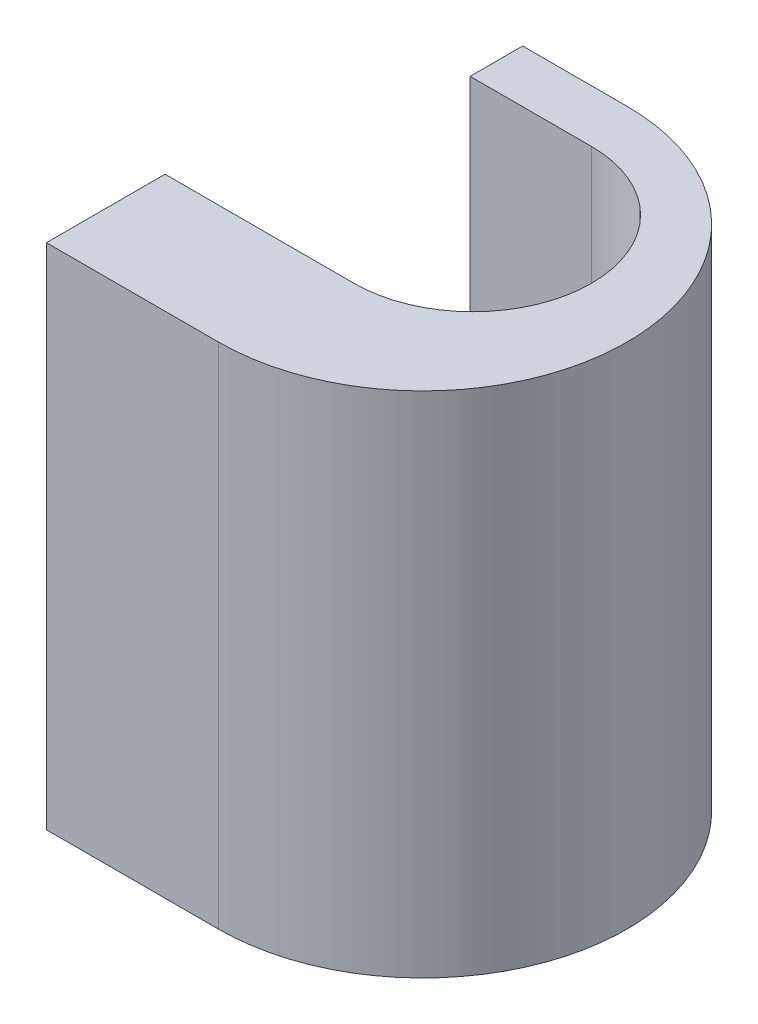
SolidWorks part; units mm, degrees
ref_plane "Front Plane" through (0, 0, 0) normal (0, 0, 1) x (1, 0, 0)
ref_plane "Top Plane" through (0, 0, 0) normal (0, 1, 0) x (1, 0, 0)
ref_plane "Right Plane" through (0, 0, 0) normal (1, 0, 0) x (0, 0, -1)
sketch "Sketch1" plane through (0, 0, 0) normal (0, 1, 0) x (1, 0, 0)
  line L0 (-2.9358, -0.5334) -> (-2.9358, 2.9666)
  line L1 (-2.9358, -0.5334) -> (-2.9358, -4.0334)
  line L5 (-2.9358, -4.0334) -> (0.6437, -4.0334)
  line L6 (-2.9358, 2.9666) -> (0.6437, 2.9666)
  circle A2 centre (0, 0) radius 1.7
  arc A4 (0.6437, 2.9666) -> (0.6437, -4.0334) centre (0.6437, -0.5334) cw
  dimension "D1" = 3.4
  dimension "D3" = 2.9666
  dimension "D4" = 2.9358
  dimension "D2" = 3.5
extrude "Boss-Extrude2" add sketch "Sketch1" along normal blind 4
sketch "Sketch2" plane through (0, 0, 0) normal (0, 1, 0) x (1, 0, 0)
  line L0 (-2.9358, 4.5176) -> (0.1437, 4.5176)
  line L1 (0.1437, -7.5334) -> (-3.4358, -7.5334)
  line L2 (-2.9358, -4.0334) -> (0.6437, -4.0334) construction
  line L3 (0.6437, 2.9666) -> (-2.9358, 2.9666) construction
  line L8 (-2.9358, -4.0334) -> (0.6437, -4.0334)
  line L9 (0.6437, 2.9666) -> (-2.9358, 2.9666)
  line L13 (-2.9358, 4.5176) -> (-2.9358, 2.9666)
  line L14 (-3.4358, -7.5334) -> (-4.9358, -7.5334)
  line L15 (-4.9358, -7.5334) -> (-4.9358, -4.0334)
  line L16 (-4.9358, -4.0334) -> (-2.9358, -4.0334)
  arc A0 (0.1437, 4.5176) -> (0.1437, -7.5334) centre (0.1437, -1.5079) cw
  arc A1 (0.6437, -4.0334) -> (0.6437, 2.9666) centre (0.6437, -0.5334) ccw
  point P19 (-5.1884, -3.5334)
  point P21 (-4.9358, -4.0334)
  dimension "D1" = 3.5
  dimension "D2" = 1.5509
  dimension "D3" = 2
extrude "Boss-Extrude3" add sketch "Sketch2" along normal blind 15
